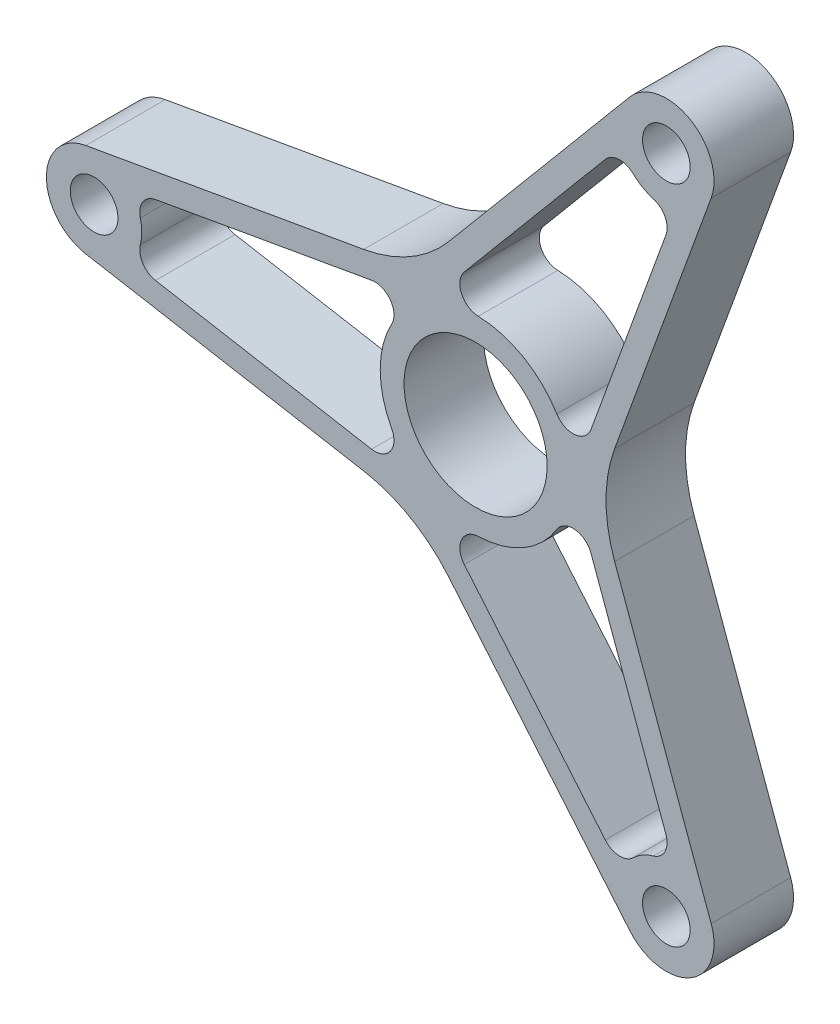
SolidWorks part; units mm, degrees
ref_plane "Front Plane" through (0, 0, 0) normal (0, 0, 1) x (1, 0, 0)
ref_plane "Top Plane" through (0, 0, 0) normal (0, 1, 0) x (1, 0, 0)
ref_plane "Right Plane" through (0, 0, 0) normal (1, 0, 0) x (0, 0, -1)
sketch "Sketch1" plane through (0, 0, 0) normal (0, 0, 1) x (1, 0, 0)
  line L0 (0, 0) -> (-48, 0) construction
  line L1 (-49.0419, 5.9088) -> (-14.0795, 12.0737)
  line L2 (-49.0419, -5.9088) -> (-14.0795, -12.0737)
  line L3 (29.6382, 39.5171) -> (17.4958, 6.1564)
  line L4 (19.4037, 45.4259) -> (-3.4164, 18.23)
  line L5 (19.4037, -45.4259) -> (-3.4164, -18.23)
  line L6 (29.6382, -39.5171) -> (17.4958, -6.1564)
  line L7 (-40.2697, 4.4093) -> (-13.0894, 9.202)
  line L8 (-40.2697, -4.4093) -> (-13.0894, -9.202)
  line L9 (23.9534, 32.6699) -> (14.5138, 6.7348)
  line L10 (16.3162, 37.0792) -> (-1.4244, 15.9367)
  line L11 (29.6382, 39.5171) -> (17.4958, 6.1564)
  line L12 (19.4037, 45.4259) -> (-3.4164, 18.23)
  line L13 (16.3162, -37.0792) -> (-1.4244, -15.9367)
  line L14 (23.9534, -32.6699) -> (14.5138, -6.7348)
  line L15 (19.4037, -45.4259) -> (-3.4164, -18.23)
  line L16 (29.6382, -39.5171) -> (17.4958, -6.1564)
  circle A0 centre (0, 0) radius 9
  circle A1 centre (0, 0) radius 48 construction
  arc A2 (-49.0419, 5.9088) -> (-49.0419, -5.9088) centre (-48, 0) ccw
  circle A3 centre (-48, 0) radius 3
  arc A4 (29.6382, 39.5171) -> (19.4037, 45.4259) centre (24, 41.5692) ccw
  circle A5 centre (24, 41.5692) radius 3
  arc A6 (18.6265, -44.2386) -> (28.9985, -38.2503) centre (24, -41.5692) ccw
  circle A7 centre (24, -41.5692) radius 3
  arc A8 (-14.0795, 12.0737) -> (-3.4164, 18.23) centre (-17.2052, 29.8002) ccw
  arc A9 (17.4958, 6.1564) -> (17.4958, -6.1564) centre (34.4103, 0) ccw
  arc A10 (-3.4164, -18.23) -> (-14.0795, -12.0737) centre (-17.2052, -29.8002) ccw
  arc A11 (-42.1807, 1.4613) -> (-42.1807, -1.4613) centre (-48, 0) cw
  arc A12 (-10.5605, 5.6987) -> (-10.5605, -5.6987) centre (0, 0) ccw
  arc A13 (-40.2697, 4.4093) -> (-42.1807, 1.4613) centre (-39.8529, 2.0458) ccw
  arc A14 (-40.2697, -4.4093) -> (-42.1807, -1.4613) centre (-39.8529, -2.0458) cw
  arc A15 (-13.0894, -9.202) -> (-10.5605, -5.6987) centre (-12.6726, -6.8384) ccw
  arc A16 (-13.0894, 9.202) -> (-10.5605, 5.6987) centre (-12.6726, 6.8384) cw
  arc A17 (10.2155, 6.2964) -> (0.3451, 11.995) centre (0, 0) ccw
  arc A18 (14.5138, 6.7348) -> (10.2155, 6.2964) centre (12.2586, 7.5556) cw
  arc A19 (-1.4244, 15.9367) -> (0.3451, 11.995) centre (0.4141, 14.394) ccw
  arc A20 (23.9534, 32.6699) -> (22.3558, 35.7989) centre (21.6982, 33.4908) ccw
  arc A21 (22.3558, 35.7989) -> (19.8248, 37.2602) centre (24, 41.5692) cw
  arc A22 (16.3162, 37.0792) -> (19.8248, 37.2602) centre (18.1547, 35.5366) cw
  circle A23 centre (24, 41.5692) radius 3
  arc A24 (29.6382, 39.5171) -> (19.4037, 45.4259) centre (24, 41.5692) ccw
  arc A25 (0.3451, -11.995) -> (10.2155, -6.2964) centre (0, 0) ccw
  arc A26 (-1.4244, -15.9367) -> (0.3451, -11.995) centre (0.4141, -14.394) cw
  arc A27 (14.5138, -6.7348) -> (10.2155, -6.2964) centre (12.2586, -7.5556) ccw
  arc A28 (16.3162, -37.0792) -> (19.8248, -37.2602) centre (18.1547, -35.5366) ccw
  arc A29 (19.8248, -37.2602) -> (22.3558, -35.7989) centre (24, -41.5692) cw
  arc A30 (23.9534, -32.6699) -> (22.3558, -35.7989) centre (21.6982, -33.4908) cw
  circle A31 centre (24, -41.5692) radius 3
  arc A32 (19.4037, -45.4259) -> (29.6382, -39.5171) centre (24, -41.5692) ccw
  point P28 (0, 0)
  point P83 (0, 0)
  dimension "D1" = 18
  dimension "D2" = 96
  dimension "D3" = 12
  dimension "D4" = 6
  dimension "D7" = 18
  dimension "D8" = 18
  dimension "D9" = 18
  dimension "D13" = 2.4
  dimension "D14" = 2.4
  dimension "D15" = 2.4
  dimension "D5" = 20
  dimension "D10" = 3
  dimension "D11" = 6
  dimension "D12" = 12
  dimension "D6" = 3
  dimension "D16" = 3
extrude "Boss-Extrude2" add sketch "Sketch1" along normal blind 10
